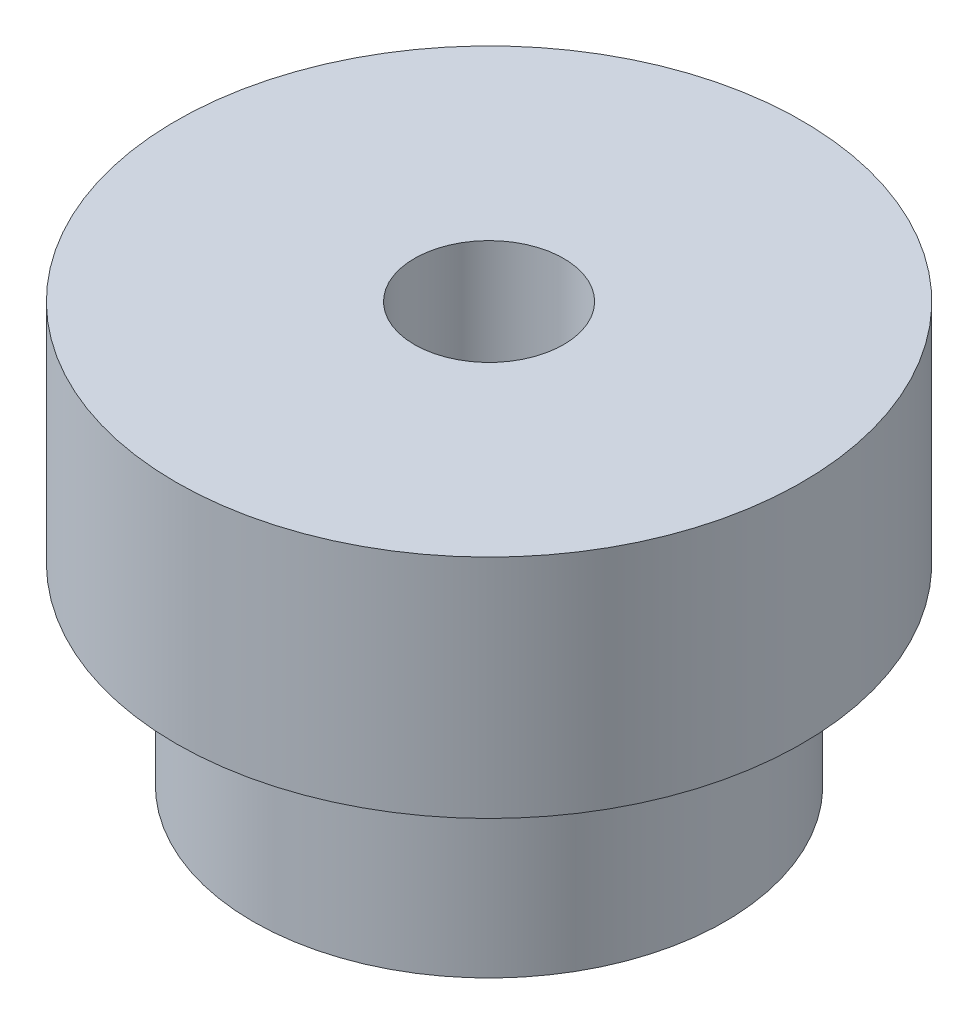
SolidWorks part; units mm, degrees
material "AISI 1020 Steel, Cold Rolled"
ref_plane "Front Plane" through (0, 0, 0) normal (0, 0, 1) x (1, 0, 0)
ref_plane "Top Plane" through (0, 0, 0) normal (0, 1, 0) x (1, 0, 0)
ref_plane "Right Plane" through (0, 0, 0) normal (1, 0, 0) x (0, 0, -1)
sketch "Sketch1" plane through (0, 0, 0) normal (0, 1, 0) x (1, 0, 0)
  circle A0 centre (0, 0) radius 12.446
  dimension "D1" = 24.892
extrude "Boss-Extrude1" add sketch "Sketch1" along normal blind 10.16
sketch "Sketch2" plane through (0, 10.16, 0) normal (0, 1, 0) x (1, 0, 0)
  circle A0 centre (0, 0) radius 16.51
  dimension "D1" = 33.02
extrude "Boss-Extrude2" add sketch "Sketch2" along normal blind 11.938
sketch "Sketch3" plane through (0, 22.098, 0) normal (0, 1, 0) x (1, 0, 0)
  circle A0 centre (0, 0) radius 3.937
  dimension "D1" = 7.874
extrude "Cut-Extrude1" cut sketch "Sketch3" against normal through all
